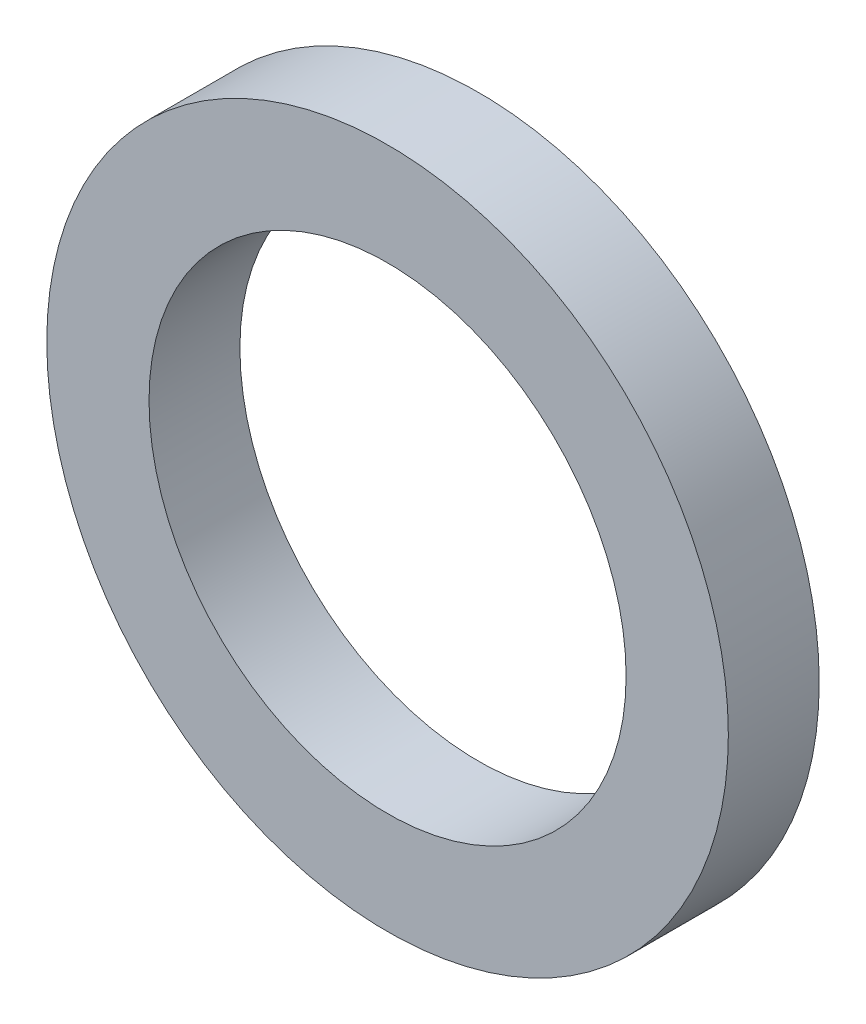
SolidWorks part; units mm, degrees
ref_plane "前视基准面" through (0, 0, 0) normal (0, 0, 1) x (1, 0, 0)
ref_plane "上视基准面" through (0, 0, 0) normal (0, 1, 0) x (1, 0, 0)
ref_plane "右视基准面" through (0, 0, 0) normal (1, 0, 0) x (0, 0, -1)
sketch "草图1" plane through (0, 0, 0) normal (0, 0, 1) x (1, 0, 0)
  circle A0 centre (0, 0) radius 30
  circle A1 centre (0, 0) radius 21
  dimension "D1" = 60
  dimension "D2" = 42
extrude "凸台-拉伸1" add sketch "草图1" along normal mid plane 8
